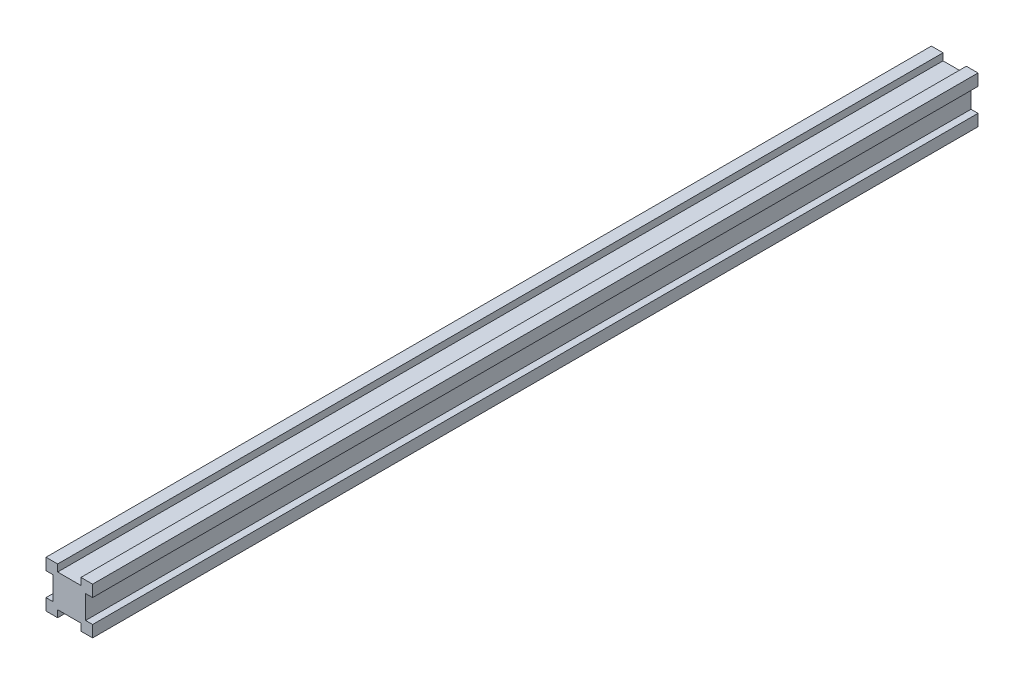
SolidWorks part; units mm, degrees
ref_plane "前视基准面" through (0, 0, 0) normal (0, 0, 1) x (1, 0, 0)
ref_plane "上视基准面" through (0, 0, 0) normal (0, 1, 0) x (1, 0, 0)
ref_plane "右视基准面" through (0, 0, 0) normal (1, 0, 0) x (0, 0, -1)
sketch "草图1" plane through (0, 0, 0) normal (0, 0, 1) x (1, 0, 0)
  line L0 (-5, 10) -> (-5, 7)
  line L1 (-10, -10) -> (10, -10)
  line L2 (-10, -10) -> (-10, -5)
  line L3 (-10, 10) -> (-5, 10)
  line L4 (10, -10) -> (10, -5)
  line L5 (-10, -10) -> (10, 10) construction
  line L6 (-10, 10) -> (10, -10) construction
  line L7 (-5, 7) -> (5, 7)
  line L8 (5, 7) -> (5, 10)
  line L9 (0, 0) -> (0, 17.8745) construction
  line L10 (7, 5) -> (7, -5)
  line L11 (10, 5) -> (7, 5)
  line L12 (7, -5) -> (10, -5)
  line L13 (5, -7) -> (-5, -7)
  line L14 (5, -10) -> (5, -7)
  line L15 (-5, -7) -> (-5, -10)
  line L16 (-7, -5) -> (-7, 5)
  line L17 (-10, -5) -> (-7, -5)
  line L18 (-7, 5) -> (-10, 5)
  line L19 (10, 5) -> (10, 10)
  line L20 (5, 10) -> (10, 10)
  line L21 (-10, 5) -> (-10, 10)
  point P0 (0, 0)
  point P27 (0, 0)
  dimension "D1" = 20
  dimension "D2" = 20
  dimension "D3" = 10
  dimension "D4" = 3
  dimension "D5" = 4
extrude "凸台-拉伸1" add sketch "草图1" along normal mid plane 380 contours L21 L18 L16 L17 L2 L1 L15 L13 L14 L4 L12 L10 L11 L19 L20 L8 L7 L0 L3
